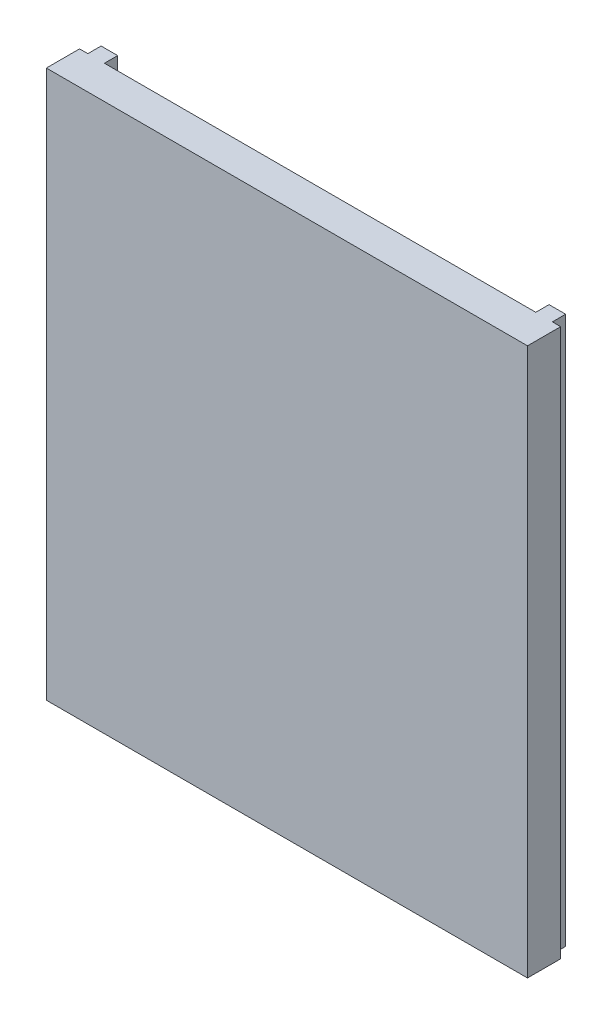
SolidWorks part; units mm, degrees
ref_plane "Front Plane" through (0, 0, 0) normal (0, 0, 1) x (1, 0, 0)
ref_plane "Top Plane" through (0, 0, 0) normal (0, 1, 0) x (1, 0, 0)
ref_plane "Right Plane" through (0, 0, 0) normal (1, 0, 0) x (0, 0, -1)
sketch "Sketch3" plane through (0, 0, 1) normal (0, 0, 1) x (1, 0, 0)
  line L1 (14.5, 16.5) -> (-14.5, 16.5)
  line L2 (14.5, 16.5) -> (14.5, -16.5)
  line L3 (14.5, -16.5) -> (-14.5, -16.5)
  line L4 (-14.5, 16.5) -> (-14.5, -16.5)
extrude "Boss-Extrude1" add sketch "Sketch3" along normal blind 2
sketch "Sketch5" plane through (0, 0, 1) normal (0, 0, -1) x (-1, 0, 0)
  line L0 (14.5, -16.5) -> (-14.5, -16.5) construction
  line L1 (13, -16.5) -> (14, -16.5)
  line L2 (13, -16.5) -> (13, 16.5)
  line L3 (13, 16.5) -> (14, 16.5)
  line L4 (14, -16.5) -> (14, 16.5)
  line L5 (13, -16.5) -> (13, 16.5) construction
  line L6 (-14.5, 16.5) -> (14.5, 16.5) construction
  line L7 (14, 16.5) -> (14, -16.5) construction
  line L8 (-13, 16.5) -> (-13, -16.5) construction
  line L9 (-13, 16.5) -> (-14, 16.5)
  line L10 (-13, 16.5) -> (-13, -16.5)
  line L11 (-13, -16.5) -> (-14, -16.5)
  line L12 (-14, 16.5) -> (-14, -16.5)
  line L13 (-14, -16.5) -> (-14, 16.5) construction
extrude "Boss-Extrude2" add sketch "Sketch5" along normal blind 0.8
